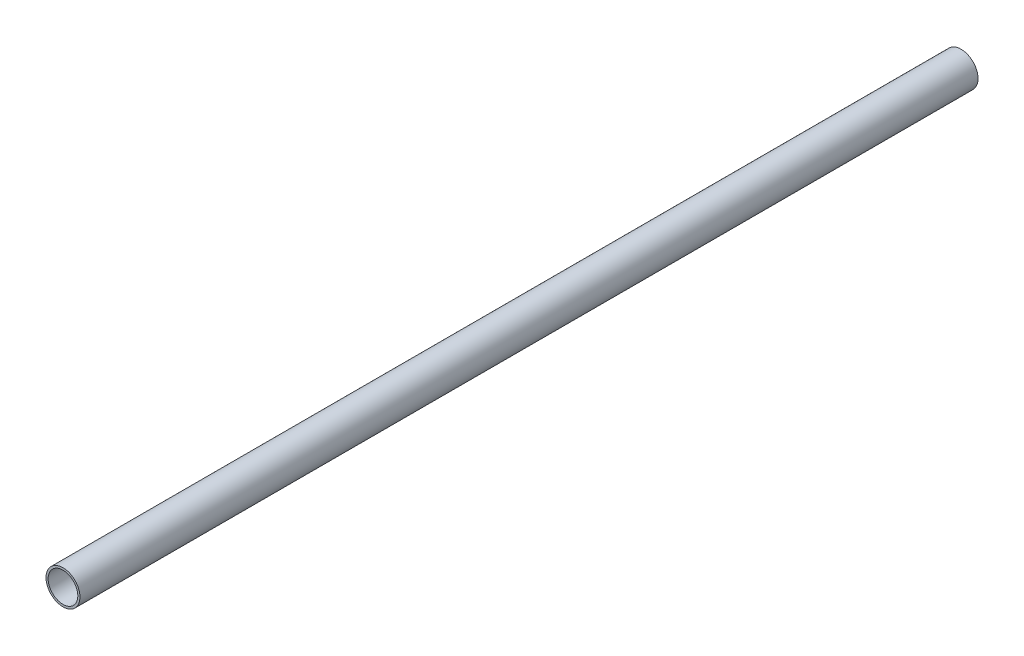
SolidWorks part; units mm, degrees
ref_plane "Alzado" through (0, 0, 0) normal (0, 0, 1) x (1, 0, 0)
ref_plane "Planta" through (0, 0, 0) normal (0, 1, 0) x (1, 0, 0)
ref_plane "Vista lateral" through (0, 0, 0) normal (1, 0, 0) x (0, 0, -1)
sketch "Croquis1" plane through (0, 0, 0) normal (0, 0, 1) x (1, 0, 0)
  circle A0 centre (0, 0) radius 7.9375
  circle A1 centre (0, 0) radius 6.9375
  dimension "D1" = 15.875
  dimension "D2" = 1
extrude "Saliente-Extruir1" add sketch "Croquis1" along normal mid plane 420
